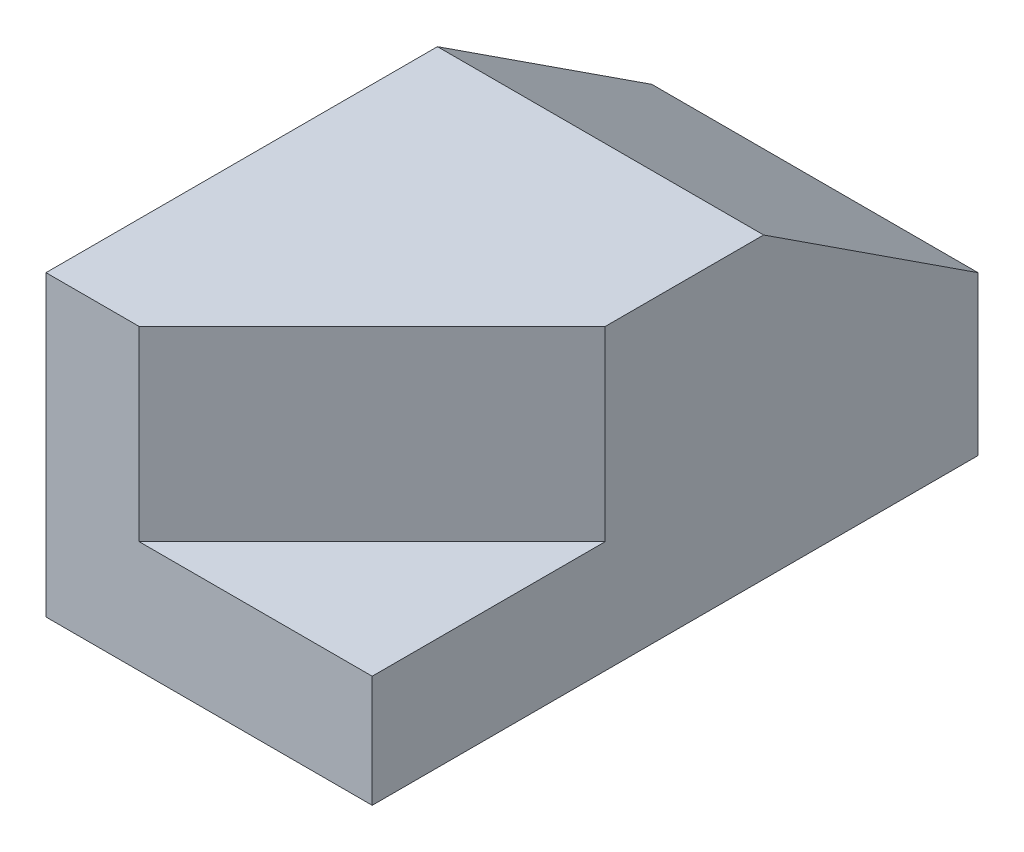
SolidWorks part; units mm, degrees
ref_plane "Front Plane" through (0, 0, 0) normal (0, 0, 1) x (1, 0, 0)
ref_plane "Top Plane" through (0, 0, 0) normal (0, 1, 0) x (1, 0, 0)
ref_plane "Right Plane" through (0, 0, 0) normal (1, 0, 0) x (0, 0, -1)
sketch "Sketch1" plane through (0, 0, 0) normal (1, 0, 0) x (0, 0, -1)
  line L0 (9.5, 16) -> (32.5, 1)
  line L1 (-32.5, -16) -> (32.5, -16)
  line L2 (-32.5, -16) -> (-32.5, 16)
  line L3 (-32.5, 16) -> (32.5, 16)
  line L4 (32.5, -16) -> (32.5, 16)
  line L5 (-32.5, -16) -> (32.5, 16) construction
  line L6 (-32.5, 16) -> (32.5, -16) construction
  point P0 (0, 0)
  dimension "D1" = 65
  dimension "D2" = 32
  dimension "D3" = 42
  dimension "D4" = 15
extrude "Boss-Extrude1" add sketch "Sketch1" along normal blind 35 contours L1 L4 L0 L3 L2
sketch "Sketch2" plane through (0, 16, 0) normal (0, 1, 0) x (1, 0, 0)
  line L0 (35, -7.5) -> (10, -32.5)
  line L3 (35, -32.5) -> (35, 9.5) construction
  line L4 (35, -32.5) -> (0, -32.5) construction
  point P6 (0, 0)
  dimension "D1" = 25
  dimension "D2" = 10
extrude "Cut-Extrude1" cut sketch "Sketch2" against normal blind 20 and the other way through all
